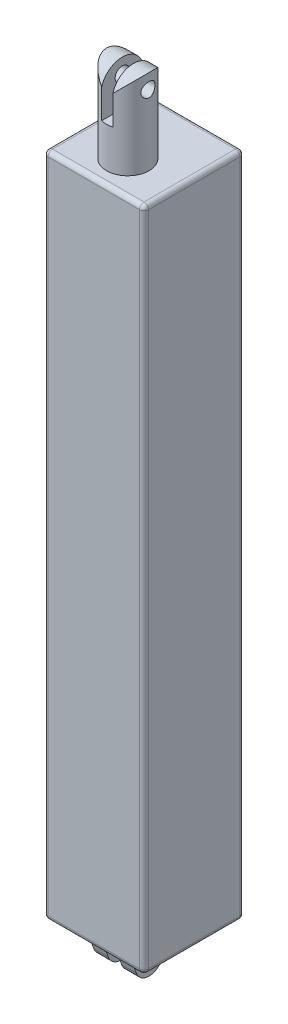
SolidWorks part; units mm, degrees
ref_plane "Front" through (0, 0, 0) normal (0, 0, 1) x (1, 0, 0)
ref_plane "Top" through (0, 0, 0) normal (0, 1, 0) x (1, 0, 0)
ref_plane "Right" through (0, 0, 0) normal (1, 0, 0) x (0, 0, -1)
sketch "Sketch1" plane through (0, 0, 0) normal (0, 1, 0) x (1, 0, 0)
  line L1 (-22.479, -22.479) -> (22.479, -22.479)
  line L2 (-22.479, -22.479) -> (-22.479, 22.479)
  line L3 (-22.479, 22.479) -> (22.479, 22.479)
  line L4 (22.479, -22.479) -> (22.479, 22.479)
  line L5 (-22.479, -22.479) -> (22.479, 22.479) construction
  line L6 (-22.479, 22.479) -> (22.479, -22.479) construction
  point P0 (0, 0)
  dimension "D1" = 44.958
  dimension "D2" = 44.958
extrude "Boss-Extrude1" add sketch "Sketch1" along normal blind 298.45
sketch "Sketch2" plane through (0, 298.45, 0) normal (0, 1, 0) x (1, 0, 0)
  line L0 (-22.479, -22.479) -> (22.479, -22.479) construction
  line L1 (0, -7.239) -> (0, -22.479) construction
  circle A0 centre (0, -7.239) radius 9.525
  dimension "D1" = 19.05
  dimension "D2" = 15.24
extrude "Boss-Extrude2" add sketch "Sketch2" along normal blind 38.1
sketch "Sketch3" plane through (-22.479, 0, 0) normal (-1, 0, 0) x (0, 0, 1)
  line L0 (-2.286, 327.025) -> (-2.286, 352.425)
  line L1 (-2.286, 352.425) -> (16.764, 352.425)
  line L2 (16.764, 352.425) -> (16.764, 327.025)
  line L3 (-2.286, 336.55) -> (-2.286, 298.45) construction
  line L4 (16.764, 298.45) -> (16.764, 336.55) construction
  line L5 (16.764, 336.55) -> (-2.286, 336.55) construction
  arc A0 (-2.286, 327.025) -> (16.764, 327.025) centre (7.239, 327.025) cw
  point P3 (0, 0)
  point P11 (7.239, 336.55)
  dimension "D1" = 25.4
extrude "Cut-Extrude1" cut sketch "Sketch3" against normal through all both and the other way through all
sketch "Sketch4" plane through (-22.479, 0, 0) normal (-1, 0, 0) x (0, 0, 1)
  line L0 (7.239, 329.946) -> (7.239, 298.45) construction
  line L1 (-22.479, 298.45) -> (22.479, 298.45) construction
  line L2 (16.764, 298.45) -> (-2.286, 298.45) construction
  circle A0 centre (7.239, 329.946) radius 3.175
  point P2 (0, 0)
  point P6 (0, 0)
  point P7 (0, 0)
  dimension "D1" = 6.35
  dimension "D2" = 31.496
extrude "Cut-Extrude2" cut sketch "Sketch4" against normal through all both and the other way through all
ref_plane "Plane1" through (0, 348.45, 0) normal (0, 1, 0) x (1, 0, 0)
sketch "Sketch5" plane through (0, 348.45, 0) normal (0, 1, 0) x (1, 0, 0)
  line L1 (-2.5, 2.761) -> (2.5, 2.761)
  line L2 (-2.5, 2.761) -> (-2.5, -17.239)
  line L3 (-2.5, -17.239) -> (2.5, -17.239)
  line L4 (2.5, 2.761) -> (2.5, -17.239)
  line L5 (-2.5, 2.761) -> (2.5, -17.239) construction
  line L6 (-2.5, -17.239) -> (2.5, 2.761) construction
  circle A1 centre (0, -7.239) radius 9.525 construction
  point P0 (0, -7.239)
  point P5 (0, 0)
  dimension "D1" = 20
  dimension "D2" = 5
extrude "Cut-Extrude3" cut sketch "Sketch5" against normal blind 32
sketch "Sketch6" plane through (0, 0, 0) normal (1, 0, 0) x (0, 0, -1)
  line L0 (2.1141, 0) -> (-16.5921, 0)
  line L1 (-16.5921, 0) -> (-12.9674, -9.959)
  line L2 (2.1141, 0) -> (-1.5106, -9.959)
  line L3 (22.479, 0) -> (-22.479, 0) construction
  line L4 (-7.239, -13.97) -> (-7.239, -7.874) construction
  line L5 (-7.239, -7.874) -> (-7.239, 329.946) construction
  arc A0 (-12.9674, -9.959) -> (-1.5106, -9.959) centre (-7.239, -7.874) ccw
  circle A1 centre (-7.239, -7.874) radius 3.175
  circle A2 centre (-7.239, 329.946) radius 3.175 construction
  point P9 (-7.239, -13.97)
  point P10 (0, 0)
  dimension "D5" = 6.35
  dimension "D1" = 7.874
  dimension "D2" = 13.97
  dimension "D3" = 70
  dimension "D4" = 70
extrude "Boss-Extrude3" add sketch "Sketch6" along normal mid plane 19.05
sketch "Sketch7" plane through (0, 0, 0) normal (0, -1, 0) x (1, 0, 0)
  line L0 (22.479, -22.479) -> (-22.479, -22.479) construction
  line L1 (-3, 22.479) -> (3, 22.479)
  line L2 (-3, 22.479) -> (-3, -22.479)
  line L3 (-3, -22.479) -> (3, -22.479)
  line L4 (3, 22.479) -> (3, -22.479)
  line L5 (-3, 22.479) -> (3, -22.479) construction
  line L6 (-3, -22.479) -> (3, 22.479) construction
  point P0 (0, 0)
  dimension "D1" = 6
extrude "Cut-Extrude4" cut sketch "Sketch7" along normal blind 19.05
fillet "Fillet1" radius 2 12 edges at (-22.479, 298.45, 0) (-22.479, 0, 0) (22.479, 298.45, 0) (22.479, 0, 0) (22.479, 149.225, -22.479) (0, 298.45, -22.479) (-22.479, 149.225, -22.479) (0, 0, -22.479) (-22.479, 149.225, 22.479) (0, 298.45, 22.479) (22.479, 149.225, 22.479) (0, 0, 22.479)
